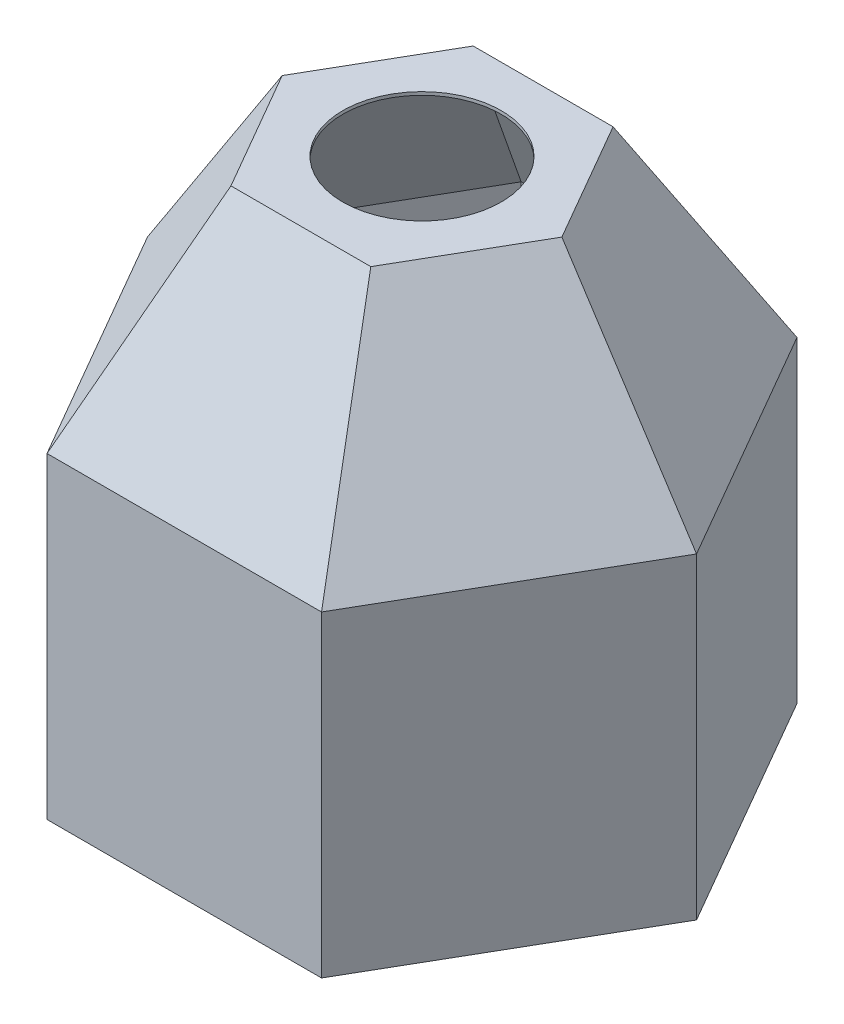
SolidWorks part; units mm, degrees
ref_plane "Front Plane" through (0, 0, 0) normal (0, 0, 1) x (1, 0, 0)
ref_plane "Top Plane" through (0, 0, 0) normal (0, 1, 0) x (1, 0, 0)
ref_plane "Right Plane" through (0, 0, 0) normal (1, 0, 0) x (0, 0, -1)
sketch "Sketch4" plane through (0, 0, 0) normal (0, 1, 0) x (1, 0, 0)
  line L1 (263.9645, 0) -> (131.9823, 228.6)
  line L2 (131.9823, 228.6) -> (-131.9823, 228.6)
  line L3 (-131.9823, 228.6) -> (-263.9645, 0)
  line L4 (-263.9645, 0) -> (-131.9823, -228.6)
  line L5 (-131.9823, -228.6) -> (131.9823, -228.6)
  line L6 (131.9823, -228.6) -> (263.9645, 0)
  circle A0 centre (0, 0) radius 228.6 construction
  dimension "D1" = 457.2
extrude "Boss-Extrude2" add sketch "Sketch4" along normal blind 304.8
ref_plane "Plane3" through (0, 503.936, 0) normal (0, 1, 0) x (1, 0, 0)
sketch "Sketch5" plane through (0, 503.936, 0) normal (0, 1, 0) x (1, 0, 0)
  line L1 (134.493, 0) -> (67.2465, 116.4744)
  line L2 (67.2465, 116.4744) -> (-67.2465, 116.4744)
  line L3 (-67.2465, 116.4744) -> (-134.493, 0)
  line L4 (-134.493, 0) -> (-67.2465, -116.4744)
  line L5 (-67.2465, -116.4744) -> (67.2465, -116.4744)
  line L6 (67.2465, -116.4744) -> (134.493, 0)
  circle A0 centre (0, 0) radius 116.4744 construction
  dimension "D1" = 268.986
loft "Loft1" add profiles "Sketch5" section "Sketch5" section face at (0, 304.8, 0)
sketch "Sketch6" plane through (0, 503.936, 0) normal (0, 1, 0) x (1, 0, 0)
  circle A0 centre (0, 0) radius 76.2
  dimension "D1" = 152.4
sketch "Sketch7" plane through (0, 0, 0) normal (0, -1, 0) x (-1, 0, 0)
  line L1 (-260.445, 0) -> (-130.2225, -225.552)
  line L2 (-130.2225, -225.552) -> (130.2225, -225.552)
  line L3 (130.2225, -225.552) -> (260.445, 0)
  line L4 (260.445, 0) -> (130.2225, 225.552)
  line L5 (130.2225, 225.552) -> (-130.2225, 225.552)
  line L6 (-130.2225, 225.552) -> (-260.445, 0)
  circle A0 centre (0, 0) radius 225.552 construction
  dimension "D1" = 451.104
extrude "Cut-Extrude1" cut sketch "Sketch7" against normal blind 304.8
sketch "Sketch8" plane through (0, 503.936, 0) normal (0, 1, 0) x (1, 0, 0)
  line L1 (130.9735, 0) -> (65.4867, 113.4264)
  line L2 (65.4867, 113.4264) -> (-65.4867, 113.4264)
  line L3 (-65.4867, 113.4264) -> (-130.9735, 0)
  line L4 (-130.9735, 0) -> (-65.4867, -113.4264)
  line L5 (-65.4867, -113.4264) -> (65.4867, -113.4264)
  line L6 (65.4867, -113.4264) -> (130.9735, 0)
  circle A0 centre (0, 0) radius 113.4264 construction
  dimension "D1" = 226.8527
sketch "Sketch9" plane through (0, 304.8, 0) normal (0, -1, 0) x (1, 0, 0)
  line L1 (260.445, 0) -> (130.2225, 225.552)
  line L2 (130.2225, 225.552) -> (-130.2225, 225.552)
  line L3 (-130.2225, 225.552) -> (-260.445, 0)
  line L4 (-260.445, 0) -> (-130.2225, -225.552)
  line L5 (-130.2225, -225.552) -> (130.2225, -225.552)
  line L6 (130.2225, -225.552) -> (260.445, 0)
  circle A0 centre (0, 0) radius 225.552 construction
loft "Cut-Loft2" cut profiles "Sketch8" section "Sketch8" section face at (0, 304.8, 0)
sketch "Sketch10" plane through (0, 503.936, 0) normal (0, 1, 0) x (1, 0, 0)
  line L1 (134.493, 0) -> (67.2465, 116.4744)
  line L2 (67.2465, 116.4744) -> (-67.2465, 116.4744)
  line L3 (-67.2465, 116.4744) -> (-134.493, 0)
  line L4 (-134.493, 0) -> (-67.2465, -116.4744)
  line L5 (-67.2465, -116.4744) -> (67.2465, -116.4744)
  line L6 (67.2465, -116.4744) -> (134.493, 0)
  circle A0 centre (0, 0) radius 116.4744 construction
extrude "Boss-Extrude3" add sketch "Sketch10" against normal blind 3.048
sketch "Sketch11" plane through (0, 503.936, 0) normal (0, 1, 0) x (1, 0, 0)
  circle A0 centre (0, 0) radius 76.2
extrude "Cut-Extrude2" cut sketch "Sketch11" against normal blind 3.048
sketch "Sketch13" plane through (0, 0, 0) normal (0, -1, 0) x (-1, 0, 0)
  line L1 (-260.445, 0) -> (-130.2225, -225.552)
  line L2 (-130.2225, -225.552) -> (130.2225, -225.552)
  line L3 (130.2225, -225.552) -> (260.445, 0)
  line L4 (260.445, 0) -> (130.2225, 225.552)
  line L5 (130.2225, 225.552) -> (-130.2225, 225.552)
  line L6 (-130.2225, 225.552) -> (-260.445, 0)
  circle A0 centre (0, 0) radius 225.552 construction
extrude "Boss-Extrude4" add sketch "Sketch13" against normal blind 3.048
